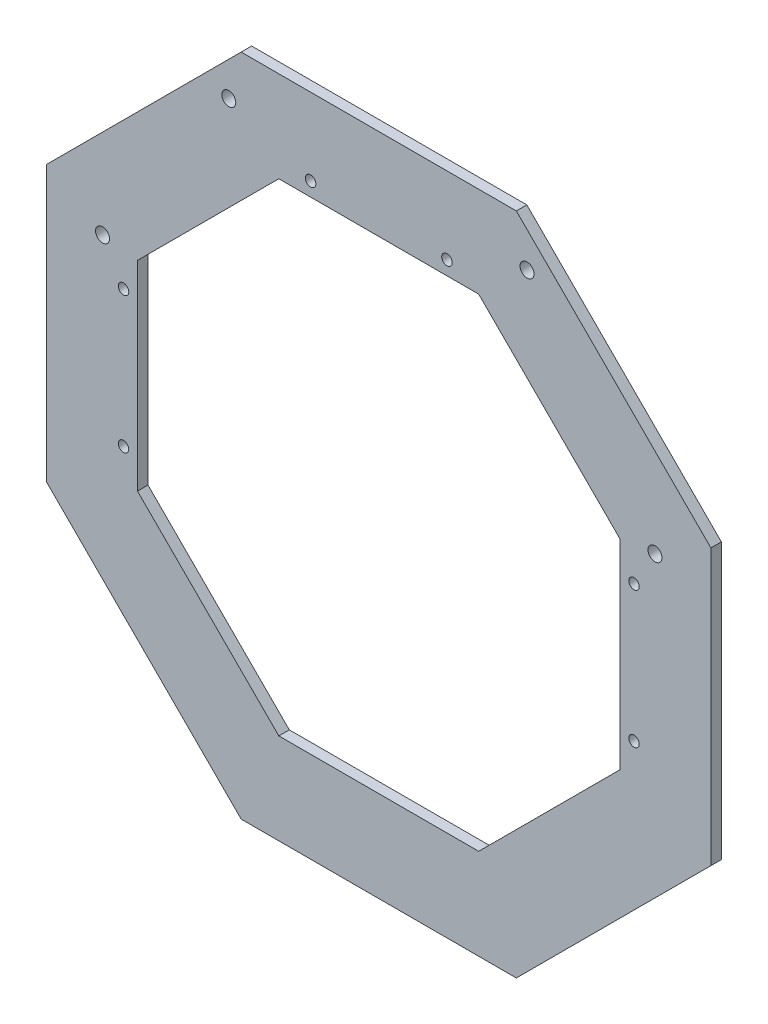
SolidWorks part; units mm, degrees
ref_plane "Alzado" through (0, 0, 0) normal (0, 0, 1) x (1, 0, 0)
ref_plane "Planta" through (0, 0, 0) normal (0, 1, 0) x (1, 0, 0)
ref_plane "Vista lateral" through (0, 0, 0) normal (1, 0, 0) x (0, 0, -1)
sketch "Croquis1" plane through (0, 0, 0) normal (0, 0, 1) x (1, 0, 0)
  line L0 (-39.3503, -95) -> (39.3503, -95)
  line L1 (95, -39.3503) -> (95, 39.3503)
  line L2 (95, 39.3503) -> (39.3503, 95)
  line L3 (39.3503, 95) -> (-39.3503, 95)
  line L4 (-39.3503, 95) -> (-95, 39.3503)
  line L5 (-95, 39.3503) -> (-95, -39.3503)
  line L6 (-95, -39.3503) -> (-39.3503, -95)
  line L7 (39.3503, -95) -> (95, -39.3503)
  line L8 (0, 0) -> (0, 125.6543) construction
  circle A0 centre (0, 0) radius 95 construction
  dimension "D1" = 190
  dimension "D2" = 45
extrude "Saliente-Extruir1" add sketch "Croquis1" along normal blind 3 contours L4 L5 L6 L0 L7 L1 L2 L3
sketch "Croquis2" plane through (0, 0, 0) normal (0, 0, -1) x (-1, 0, 0)
  line L1 (-69, -28.5807) -> (-28.5807, -69)
  line L2 (-28.5807, -69) -> (28.5807, -69)
  line L3 (28.5807, -69) -> (69, -28.5807)
  line L4 (69, -28.5807) -> (69, 28.5807)
  line L5 (69, 28.5807) -> (28.5807, 69)
  line L6 (28.5807, 69) -> (-28.5807, 69)
  line L7 (-28.5807, 69) -> (-69, 28.5807)
  line L8 (-69, 28.5807) -> (-69, -28.5807)
  line L10 (-95, 39.3503) -> (-39.3503, 95) construction
  circle A0 centre (0, 0) radius 69 construction
  dimension "D1" = 138
  dimension "D2" = 0
extrude "Cortar-Extruir1" cut sketch "Croquis2" against normal blind 3
sketch "Croquis3" plane through (0, 0, 0) normal (0, 0, -1) x (-1, 0, 0)
  line L1 (28.5807, 69) -> (-28.5807, 69) construction
  line L2 (0, 0) -> (0, 95) construction
  line L3 (-39.3503, 95) -> (39.3503, 95) construction
  line L4 (-69, 28.5807) -> (-69, -28.5807) construction
  line L5 (0, 0) -> (-95, 0) construction
  line L6 (-95, -39.3503) -> (-95, 39.3503) construction
  circle A0 centre (-19.5, 73) radius 1.5
  circle A1 centre (19.5, 73) radius 1.5
  circle A2 centre (-73, 19.5) radius 1.5
  circle A3 centre (-73, -19.5) radius 1.5
  circle A4 centre (73, 19.5) radius 1.5
  circle A5 centre (73, -19.5) radius 1.5
  dimension "D1" = 3
  dimension "D2" = 3
  dimension "D3" = 39
  dimension "D4" = 4
  dimension "D5" = 19.5
  dimension "D6" = 19.5
  dimension "D7" = 3
  dimension "D8" = 3
  dimension "D9" = 4
  dimension "D10" = 4
  dimension "D11" = 39
  dimension "D12" = 19.5
extrude "Cortar-Extruir2" cut sketch "Croquis3" against normal through all
sketch "Croquis5" plane through (0, 0, 3) normal (0, 0, 1) x (1, 0, 0)
  line L0 (39.3503, 95) -> (-39.3503, 95) construction
  line L1 (0, 0) -> (0, 95) construction
  line L3 (-69, 28.5807) -> (-28.5807, 69) construction
  line L4 (-95, 39.3503) -> (-95, -39.3503) construction
  line L6 (28.5807, 69) -> (69, 28.5807) construction
  circle A0 centre (-42.8922, 81.7) radius 2
  circle A1 centre (42.4094, 81.9) radius 2
  circle A2 centre (-79, 29.8944) radius 2
  circle A4 centre (79, 29.8944) radius 2
  dimension "D1" = 4
  dimension "D2" = 4
  dimension "D3" = 13.3
  dimension "D4" = 18.9
  dimension "D5" = 19.1
  dimension "D6" = 13.1
  dimension "D7" = 4
  dimension "D8" = 8
  dimension "D9" = 16
extrude "Cortar-Extruir3" cut sketch "Croquis5" against normal through all
